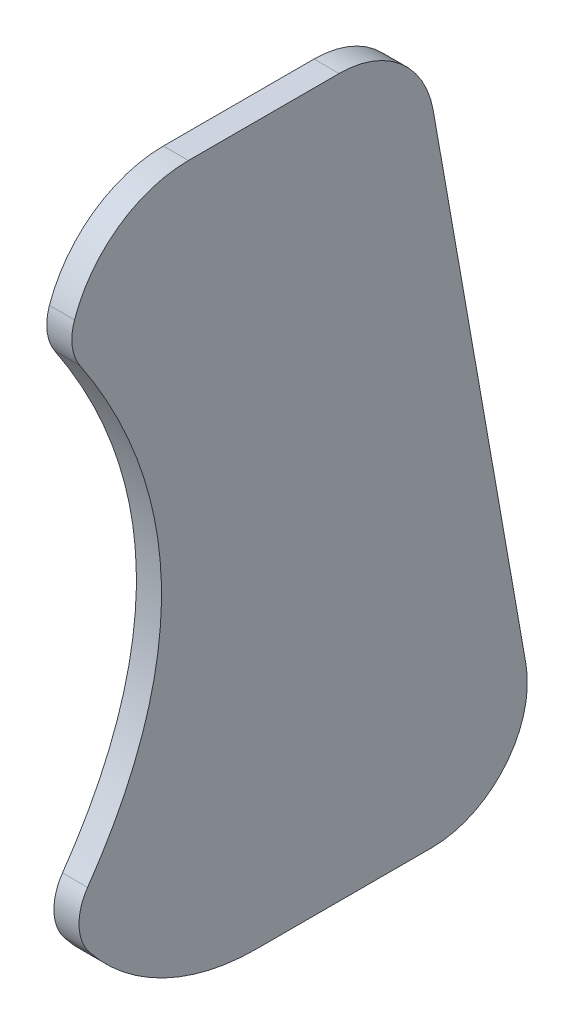
SolidWorks part; units mm, degrees
material "ABS"
ref_plane "Front Plane" through (0, 0, 0) normal (0, 0, 1) x (1, 0, 0)
ref_plane "Top Plane" through (0, 0, 0) normal (0, 1, 0) x (1, 0, 0)
ref_plane "Right Plane" through (0, 0, 0) normal (1, 0, 0) x (0, 0, -1)
sketch "Sketch1" plane through (0, 0, 0) normal (1, 0, 0) x (0, 0, -1)
  line L0 (-0.8588, 31.1045) -> (27.0812, 31.1045)
  line L1 (42.0897, 48.9909) -> (27.3099, 132.8109)
  line L2 (12.3015, 145.4045) -> (-11.7141, 145.4045)
  arc A0 (27.0812, 31.1045) -> (42.0897, 48.9909) centre (27.0812, 46.3445) ccw
  arc A1 (27.3099, 132.8109) -> (12.3015, 145.4045) centre (12.3015, 130.1645) ccw
  arc A2 (-0.8588, 31.1045) -> (-30.8268, 48.9909) centre (-0.8588, 65.1529) cw
  arc A3 (-11.7141, 145.4045) -> (-30.8268, 128.3595) centre (-11.7141, 126.1663) ccw
  spline S0 degree 2 poles (-30.8268, 128.3595) (-1.2094, 86.6475) (-30.8268, 48.9909) knots 0 0 0 1 1 1
  point P6 (45.2435, 31.1045)
  point P9 (32.8238, 145.4045)
  point P15 (-43.5811, 29.6195)
  dimension "D4" = 15.24
  dimension "D1" = 27.94
  dimension "D2" = 80
  dimension "D3" = 114.3
extrude "Boss-Extrude1" add sketch "Sketch1" along normal blind 4
fillet "Fillet1" radius 7.62 1 edges at (2, 128.3595, 30.8268)
fillet "Fillet2" radius 7.62 1 edges at (2, 48.9909, 30.8268)
